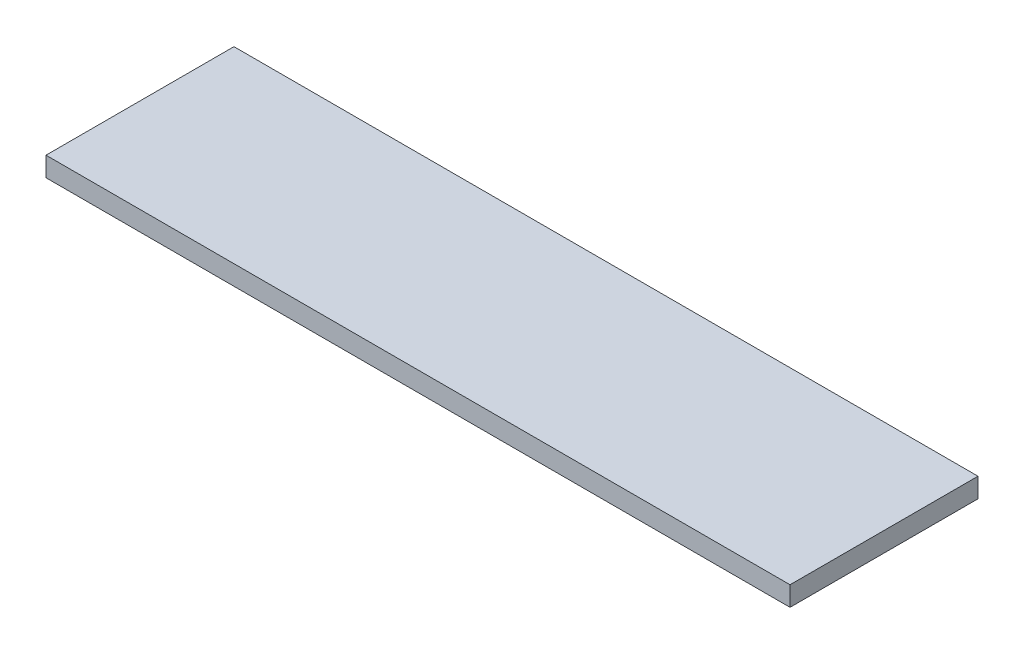
SolidWorks part; units mm, degrees
ref_plane "Front" through (0, 0, 0) normal (0, 0, 1) x (1, 0, 0)
ref_plane "Top" through (0, 0, 0) normal (0, 1, 0) x (1, 0, 0)
ref_plane "Right" through (0, 0, 0) normal (1, 0, 0) x (0, 0, -1)
sketch "Sketch1" plane through (0, 0, 0) normal (0, 1, 0) x (1, 0, 0)
  line L1 (-2413, 609.6) -> (2413, 609.6)
  line L2 (-2413, 609.6) -> (-2413, -609.6)
  line L3 (-2413, -609.6) -> (2413, -609.6)
  line L4 (2413, 609.6) -> (2413, -609.6)
  line L5 (-2413, 609.6) -> (2413, -609.6) construction
  line L6 (-2413, -609.6) -> (2413, 609.6) construction
  point P0 (0, 0)
  dimension "D1" = 4826
  dimension "D2" = 1219.2
extrude "Boss-Extrude1" add sketch "Sketch1" along normal blind 127
sketch "Sketch2" plane through (0, 127, 0) normal (0, 1, 0) x (1, 0, 0)
  line L0 (2413, -609.6) -> (2413, 609.6) construction
  line L1 (-2413, 609.6) -> (2413, 609.6)
  line L2 (-2413, 609.6) -> (-2413, -25.4)
  line L3 (-2413, -25.4) -> (2413, -25.4)
  line L4 (2413, 609.6) -> (2413, -25.4)
  line L5 (-2413, -609.6) -> (2413, -609.6) construction
  dimension "D1" = 584.2
extrude "Cut-Extrude1" [suppressed] cut sketch "Sketch2" against normal through all
